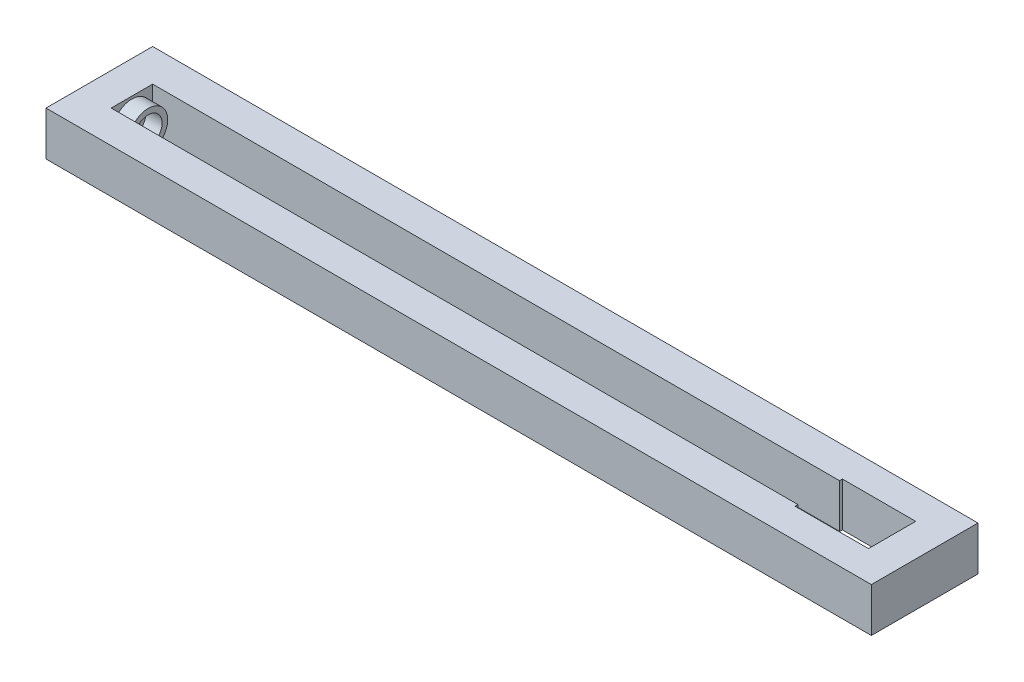
SolidWorks part; units mm, degrees
material "201 Annealed Stainless Steel (SS)"
ref_plane "Front Plane" through (0, 0, 0) normal (0, 0, 1) x (1, 0, 0)
ref_plane "Top Plane" through (0, 0, 0) normal (0, 1, 0) x (1, 0, 0)
ref_plane "Right Plane" through (0, 0, 0) normal (1, 0, 0) x (0, 0, -1)
sketch "Sketch1" plane through (0, 0, 0) normal (0, 1, 0) x (1, 0, 0)
  line L0 (-380, 49.1) -> (380, 49.1)
  line L1 (-350, 19.1) -> (350, 19.1)
  line L2 (-350, 19.1) -> (-350, -19.1)
  line L3 (-350, -19.1) -> (350, -19.1)
  line L4 (350, 19.1) -> (350, -19.1)
  line L5 (-350, 19.1) -> (350, -19.1) construction
  line L6 (-350, -19.1) -> (350, 19.1) construction
  line L7 (380, 49.1) -> (380, -49.1)
  line L8 (-380, -49.1) -> (380, -49.1)
  line L9 (-380, 49.1) -> (-380, -49.1)
  point P0 (0, 0)
  dimension "D1" = 38.2
  dimension "D2" = 700
  dimension "D3" = 30
extrude "Boss-Extrude3" add sketch "Sketch1" along normal blind 40.64
sketch "Sketch2" plane through (0, 0, 0) normal (0, -1, 0) x (1, 0, 0)
  line L1 (-350, 19.1) -> (350, 19.1)
  line L2 (-350, 19.1) -> (-350, -19.1)
  line L3 (-350, -19.1) -> (350, -19.1)
  line L4 (350, 19.1) -> (350, -19.1)
  line L5 (-350, 19.1) -> (350, -19.1) construction
  line L6 (-350, -19.1) -> (350, 19.1) construction
  point P0 (0, 0)
extrude "Boss-Extrude4" add sketch "Sketch2" against normal blind 0.254
sketch "Sketch3" plane through (0, 40.64, 0) normal (0, 1, 0) x (1, 0, 0)
  line L0 (380, 0) -> (143.674, 0) construction
  line L1 (350, 21.75) -> (282.5, 21.75)
  line L2 (350, 21.75) -> (350, -21.75)
  line L3 (350, -21.75) -> (282.5, -21.75)
  line L4 (282.5, 21.75) -> (282.5, -21.75)
  line L5 (380, -49.1) -> (380, 49.1) construction
  line L6 (350, -19.1) -> (350, 19.1) construction
  point P9 (350, 0)
  dimension "D1" = 43.5
  dimension "D2" = 67.5
  dimension "D3" = 0
extrude "Cut-Extrude1" cut sketch "Sketch3" against normal up to surface (40.386 mm away) up to face at (0, 0.254, 0)
sketch "Sketch5" plane through (0, 40.64, 0) normal (0, 1, 0) x (1, 0, 0)
  line L1 (282.5, 21.75) -> (350, 21.75)
  line L2 (282.5, 21.75) -> (282.5, -21.75)
  line L3 (282.5, -21.75) -> (350, -21.75)
  line L4 (350, 21.75) -> (350, -21.75)
extrude "Cut-Extrude5" cut sketch "Sketch5" against normal up to next
sketch "Sketch6" plane through (-350, 0, 0) normal (1, 0, 0) x (0, 0, -1)
  line L0 (0, 43.1998) -> (0, -9.7567) construction
  line L1 (49.1, 20.32) -> (-49.1, 20.32) construction
  line L2 (49.1, 40.64) -> (49.1, 0) construction
  line L3 (-49.1, 40.64) -> (-49.1, 0) construction
  circle A0 centre (0, 20.32) radius 12.8397
  circle A1 centre (0, 20.32) radius 18
  dimension "D1" = 25.6794
  dimension "D2" = 36
extrude "Boss-Extrude5" add sketch "Sketch6" along normal blind 15
